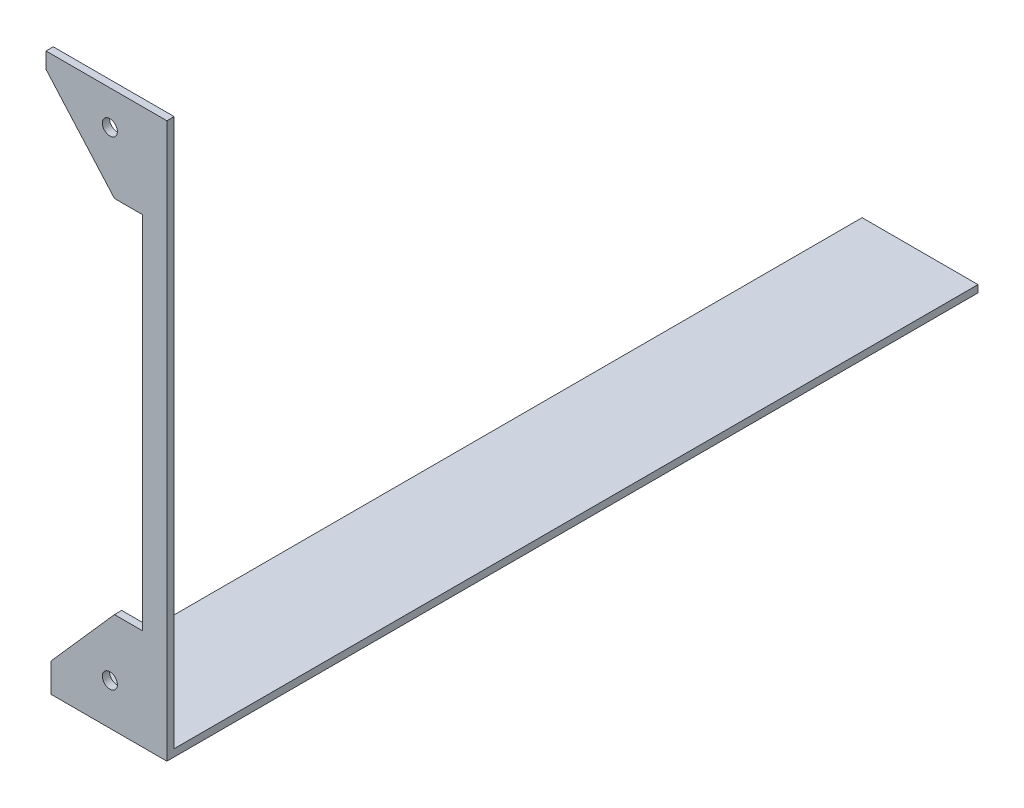
SolidWorks part; units mm, degrees
ref_plane "Front Plane" through (0, 0, 0) normal (0, 0, 1) x (1, 0, 0)
ref_plane "Top Plane" through (0, 0, 0) normal (0, 1, 0) x (1, 0, 0)
ref_plane "Right Plane" through (0, 0, 0) normal (1, 0, 0) x (0, 0, -1)
sketch "Sketch1" plane through (0, 0, 0) normal (0, 0, 1) x (1, 0, 0)
  line L0 (-250, 120) -> (0, 120) construction
  line L1 (0, 118) -> (0, 2) construction
  line L2 (0, 0) -> (-250, 0) construction
  line L3 (-26.5, 116.5) -> (-11.5, 99.5) construction
  line L4 (-11.5, 99.5) -> (-5.4, 99.5) construction
  line L5 (-5.4, 99.5) -> (-5.4, 20.5) construction
  line L6 (-11.5, 20.5) -> (-26.5, 3.5) construction
  line L7 (-5.4, 20.5) -> (-11.5, 20.5) construction
  line L8 (-26.5, 120) -> (0, 120)
  line L9 (0, 120) -> (0, 0)
  line L10 (0, 0) -> (-26.5, 0)
  line L11 (-26.5, 116.5) -> (-11.5, 99.5)
  line L12 (-11.5, 99.5) -> (-5.4, 99.5)
  line L13 (-5.4, 99.5) -> (-5.4, 20.5)
  line L14 (-11.5, 20.5) -> (-26.5, 3.5)
  line L15 (-5.4, 20.5) -> (-11.5, 20.5)
  line L16 (-26.5, 3.5) -> (-26.5, 0)
  line L17 (-26.5, 116.5) -> (-26.5, 120)
  line L18 (-25.4, 4.7467) -> (-25.4, 0)
  arc A0 (-14.15, 112.5) -> (-10.85, 112.5) centre (-12.5, 112.5) ccw construction
  arc A1 (-10.85, 112.5) -> (-14.15, 112.5) centre (-12.5, 112.5) ccw construction
  arc A2 (-14.15, 7.5) -> (-10.85, 7.5) centre (-12.5, 7.5) ccw construction
  arc A3 (-10.85, 7.5) -> (-14.15, 7.5) centre (-12.5, 7.5) ccw construction
  arc A4 (-14.15, 112.5) -> (-10.85, 112.5) centre (-12.5, 112.5) ccw
  arc A5 (-10.85, 112.5) -> (-14.15, 112.5) centre (-12.5, 112.5) ccw
  arc A6 (-14.15, 7.5) -> (-10.85, 7.5) centre (-12.5, 7.5) ccw
  arc A7 (-10.85, 7.5) -> (-14.15, 7.5) centre (-12.5, 7.5) ccw
  dimension "D1" = 25.4
extrude "Boss-Extrude1" add sketch "Sketch1" along normal blind 1.5875 contours L14 L18 L10 L9 L8 L17 L11 L12 L13 L15 A7 A6 A5 A4
sketch "Sketch2" plane through (0, 0, 0) normal (0, 1, 0) x (1, 0, 0)
  line L0 (0, -1.5875) -> (0, 176.2125)
  line L1 (0, 176.2125) -> (-25.4, 176.2125)
  line L2 (-25.4, 176.2125) -> (-25.4, -1.5875)
  line L4 (0, -1.5875) -> (-25.4, -1.5875) construction
  line L5 (0, -1.5875) -> (-25.4, -1.5875)
  dimension "D1" = 177.8
extrude "Boss-Extrude2" add sketch "Sketch2" against normal blind 1.5875
